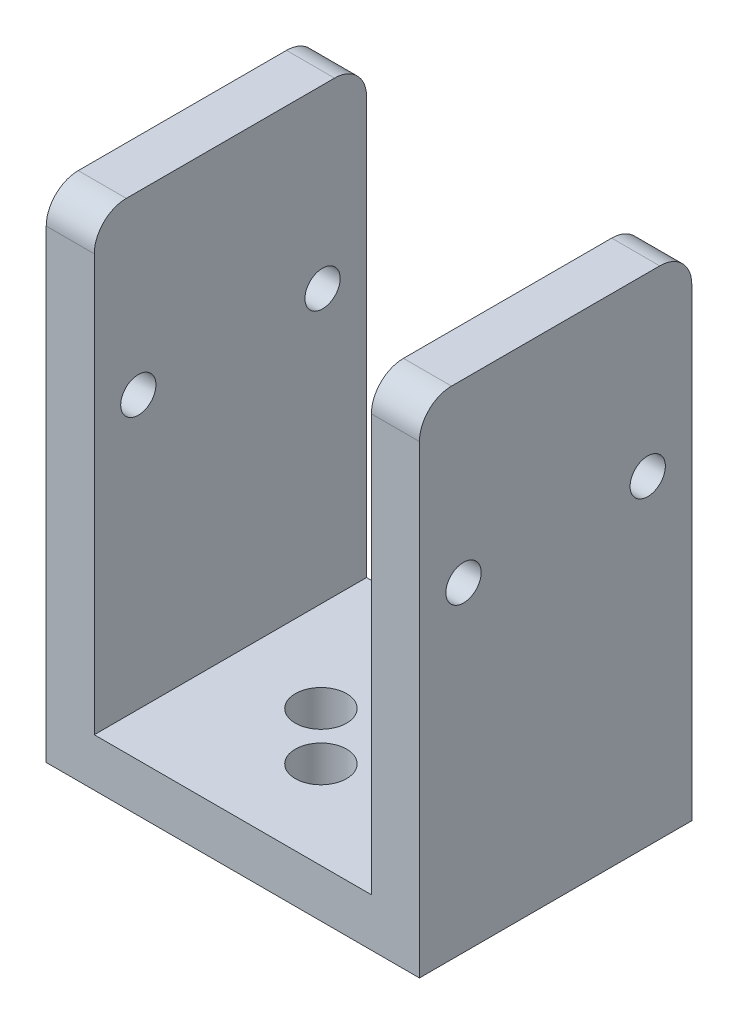
SolidWorks part; units mm, degrees
ref_plane "前视基准面" through (0, 0, 0) normal (0, 0, 1) x (1, 0, 0)
ref_plane "上视基准面" through (0, 0, 0) normal (0, 1, 0) x (1, 0, 0)
ref_plane "右视基准面" through (0, 0, 0) normal (1, 0, 0) x (0, 0, -1)
sketch "草图1" plane through (0, 0, 0) normal (0, 1, 0) x (1, 0, 0)
  line L0 (0, 0) -> (6.5796, 0) construction
  line L1 (-8.65, -8.5) -> (8.65, -8.5)
  line L2 (-8.65, -8.5) -> (-8.65, 8.5)
  line L3 (-8.65, 8.5) -> (8.65, 8.5)
  line L4 (8.65, -8.5) -> (8.65, 8.5)
  line L5 (-8.65, -8.5) -> (8.65, 8.5) construction
  line L6 (-8.65, 8.5) -> (8.65, -8.5) construction
  line L7 (0, 0) -> (0, 5.5116) construction
  circle A0 centre (0, 3) radius 1.6
  circle A1 centre (3, 0) radius 1.6
  circle A2 centre (0, -3) radius 1.6
  circle A3 centre (-3, 0) radius 1.6
  point P0 (0, 0)
  dimension "D3" = 3
  dimension "D1" = 17
  dimension "D2" = 17.3
  dimension "D4" = 3
extrude "凸台-拉伸1" add sketch "草图1" along normal blind 3
sketch "草图2" plane through (0, 0, 0) normal (0, 1, 0) x (1, 0, 0)
  line L0 (11.65, 8.5) -> (11.65, -8.5)
  line L1 (0, 0) -> (0, 7.5299) construction
  line L2 (8.65, 8.5) -> (8.65, 7.8287) construction
  line L3 (8.65, 8.5) -> (11.65, 8.5)
  line L4 (8.65, -8.5) -> (11.65, -8.5)
  line L5 (-8.65, -8.5) -> (-11.65, -8.5)
  line L6 (-11.65, 8.5) -> (-11.65, -8.5)
  line L7 (-8.65, 8.5) -> (-11.65, 8.5)
  line L8 (-8.65, 8.5) -> (-8.65, -8.5)
  line L9 (8.65, 8.5) -> (8.65, -8.5)
  dimension "D1" = 3
extrude "凸台-拉伸2" add sketch "草图2" along normal blind 31
fillet "圆角1" radius 2 4 edges at (10.15, 31, -8.5) (10.15, 31, 8.5) (-10.15, 31, 8.5) (-10.15, 31, -8.5)
sketch "草图3" plane through (-11.65, 0, 0) normal (-1, 0, 0) x (0, 0, 1)
  line L0 (0, 0) -> (0, 23.2419) construction
  line L1 (-8.5, 0) -> (8.5, 0) construction
  circle A0 centre (5.75, 20) radius 1.1
  circle A1 centre (-5.75, 20) radius 1.1
  dimension "D1" = 20
  dimension "D2" = 5.75
extrude "切除-拉伸1" cut sketch "草图3" against normal blind 28
